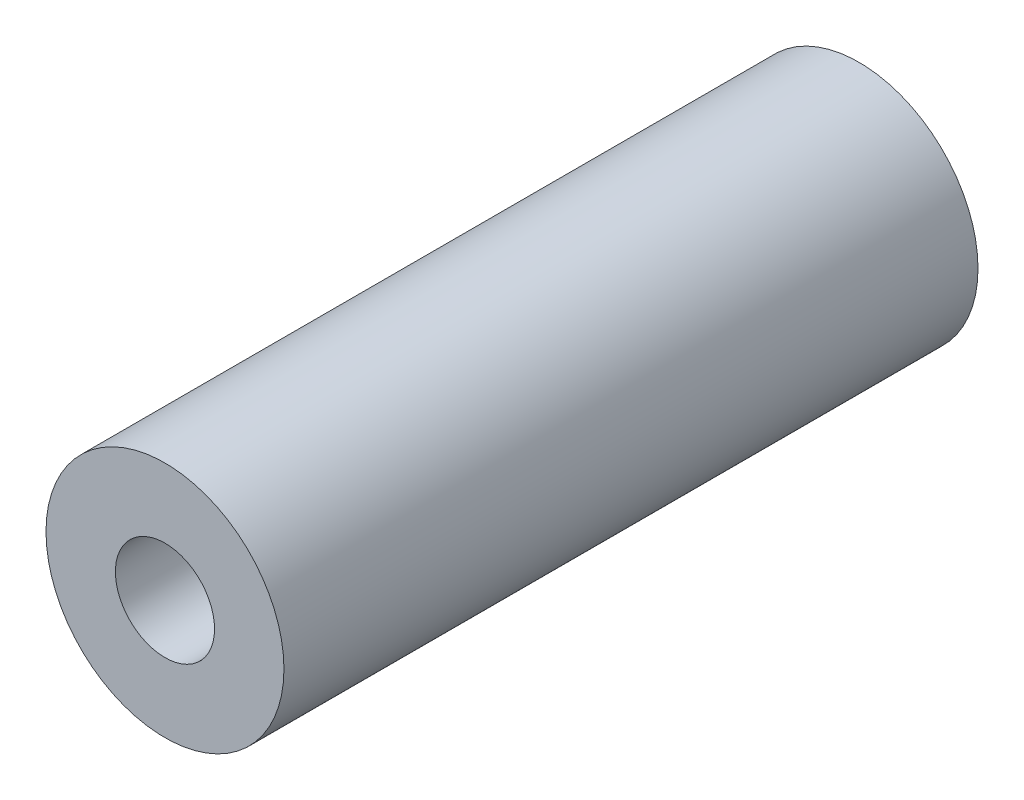
SolidWorks part; units mm, degrees
ref_plane "Front Plane" through (0, 0, 0) normal (0, 0, 1) x (1, 0, 0)
ref_plane "Top Plane" through (0, 0, 0) normal (0, 1, 0) x (1, 0, 0)
ref_plane "Right Plane" through (0, 0, 0) normal (1, 0, 0) x (0, 0, -1)
sketch "Sketch1" plane through (0, 0, 0) normal (0, 0, 1) x (1, 0, 0)
  circle A0 centre (0, 0) radius 5 construction
  circle A1 centre (0, 0) radius 5
  circle A2 centre (0, 0) radius 12
extrude "Boss-Extrude1" add sketch "Sketch1" along normal blind 70
